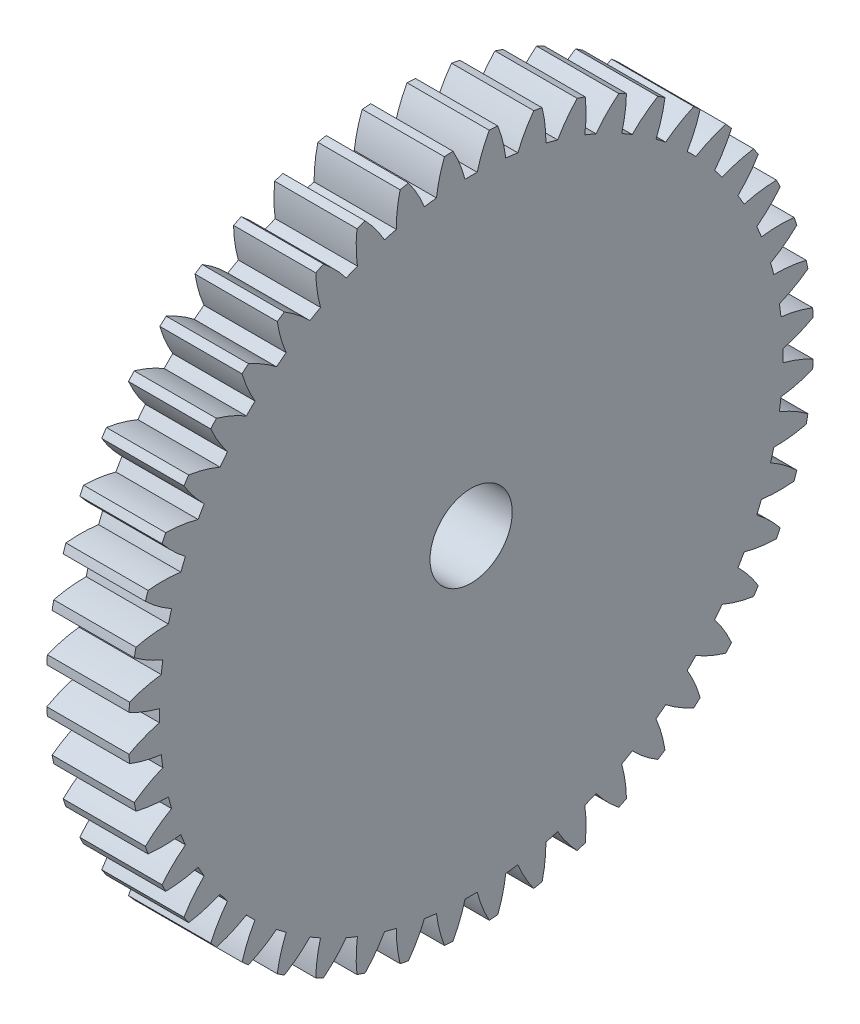
SolidWorks part; units mm, degrees
ref_plane "Plane1" through (0, 0, 0) normal (0, 0, 1) x (1, 0, 0)
ref_plane "Plane2" through (0, 0, 0) normal (0, 1, 0) x (1, 0, 0)
ref_plane "Plane3" through (0, 0, 0) normal (1, 0, 0) x (0, 0, -1)
other "Configuration Table"
sketch "HoldingSke" plane through (0, 0, 0) normal (0, 1, 0) x (1, 0, 0)
  line L0 (0, 0) -> (407.902, -453.0211)
  line L1 (-15, 0) -> (100, 0) construction
  line L2 (0, 0) -> (-2.1039, 2.3779)
  line L3 (0, 0) -> (-11.863, 4.5341)
  line L4 (0, 0) -> (5.7786, 6.4178)
  line L5 (0, 0) -> (-47.5972, -17.7524)
  line L6 (0, 0) -> (-10.5278, -7.1032)
  line L7 (-2.1039, 2.3779) -> (8.8308, 51.9871)
  line L8 (-76.2, 54.61) -> (-75.184, 54.61)
  line L9 (-71.009, 38.7566) -> (-53.1078, 45.2721)
  line L10 (-76.2, 71.12) -> (104.1128, 71.12)
  line L11 (0, 0) -> (-12.7, 0)
  line L12 (-76.2, 101.6) -> (-76.1573, 101.6)
  line L13 (24.9733, 27.94) -> (52.9518, 28.4284)
  line L14 (24.9733, 27.94) -> (25.0241, 27.9398)
  line L15 (24.9733, 27.94) -> (100.4021, 29.52)
  circle A0 centre (0, 0) radius 0.3969
  circle A1 centre (0, 0) radius 24.0792
  circle A2 centre (0, 0) radius 38.1
  circle A3 centre (0, 0) radius 0.3969
  dimension "MHD" = 48.1584
  dimension "Hub_dia" = 76.2
  dimension "Bore" = 0.7937
  dimension "MBD" = 0.7937
  dimension "Num_teeth" = 48
  dimension "Pitch" = 609.6
  dimension "Overall_len" = 50.8
  dimension "Show_teeth" = 48
  dimension "Thickness" = 12.7
  dimension "OAL" = 50.8001
  dimension "T_dim" = 1.016
  dimension "Ap" = 20
  dimension "H" = 19.05
  dimension "Pitch_radius" = 180.3128
  dimension "Width" = 12.7
  dimension "Backlash" = 0.0427
  dimension "Addendum_fac" = 1
  dimension "Dedendum_fac" = 1.2
  dimension "Clearance_fac" = 0.2
  dimension "Dedendum_add" = 0.0508
sketch "BasProSke" plane through (0, 0, 0) normal (0, 1, 0) x (1, 0, 0)
  line L0 (-10, 0) -> (60, 0) construction
  line L1 (0, 0) -> (0, 26.4583)
  line L2 (0, 0) -> (6.35, 0)
  line L3 (6.35, 0) -> (6.35, 26.4583)
  line L4 (6.35, 26.4583) -> (0, 26.4583)
  dimension "Thickness" = 6.35
  dimension "Diameter" = 52.9167
revolve "Base-Revolve" add sketch "BasProSke" angle 360 about L0
sketch "TooCutSke" plane through (0, 0, 0) normal (1, 0, 0) x (0, 0, -1)
  line L1 (0, 0) -> (0, 107) construction
  line L2 (0, 0) -> (-0.9057, 25.3838) construction
  line L3 (0, 0) -> (-3.321, 50.6688) construction
  line L4 (-0.9057, 25.3838) -> (-1.6605, 25.3344) construction
  arc A0 (0.47, 24.0746) -> (-0.47, 24.0746) centre (0, 0) ccw
  arc A1 (1.4151, 26.4459) -> (-1.4151, 26.4459) centre (0, 0) ccw
  circle A2 centre (0, 0) radius 25.4 construction
  circle A3 centre (0, 0) radius 23.8682 construction
  arc A4 (-0.47, 24.0746) -> (-1.4151, 26.4459) centre (-10.3059, 21.5286) ccw
  arc A5 (1.4151, 26.4459) -> (0.47, 24.0746) centre (10.3059, 21.5286) ccw
  dimension "Root_dia" = 48.1584
  dimension "Overcut_dia" = 52.9675
  dimension "Pitch_dia" = 50.8
  dimension "Base_dia" = 47.7364
  dimension "Flank_rad" = 10.16
  dimension "Half_ang" = 3.75
  dimension "Half_CT" = 0.7564
extrude "ToothCut" cut sketch "TooCutSke" along normal through all
fillet "Breaks" [suppressed] radius 0.0212
fillet "RootFillets" [suppressed] radius 0.2625
pattern_circular "TeethCuts" count 48 every 7.5 about axis through (-10, 0, 0) along (1, 0, 0) of "ToothCut", "RootFillets", "Breaks"
sketch "HubNeaOneSke" plane through (0, 0, 0) normal (-1, 0, 0) x (0, 0, 1)
  circle A0 centre (0, 0) radius 24.0792
  dimension "Diameter" = 48.1584
extrude "HubNearOne" [suppressed] add sketch "HubNeaOneSke" along normal blind 44.4501
sketch "HubNeaBotSke" plane through (0, 0, 0) normal (-1, 0, 0) x (0, 0, 1)
  circle A0 centre (0, 0) radius 24.0792
  dimension "Diameter" = 48.1584
extrude "HubNearBoth" [suppressed] add sketch "HubNeaBotSke" along normal blind 22.225
ref_plane "FarPln" through (6.35, 0, 0) normal (1, 0, 0) x (0, 0, -1)
sketch "HubFarSke" plane through (6.35, 0, 0) normal (1, 0, 0) x (0, 0, -1)
  circle A0 centre (0, 0) radius 24.0792
  dimension "Diameter" = 48.1584
extrude "HubFar" [suppressed] add sketch "HubFarSke" along normal blind 22.225
sketch "BorSke" plane through (0, 0, 0) normal (1, 0, 0) x (0, 0, -1)
  circle A0 centre (0, 0) radius 3.175
  dimension "Diameter" = 6.35
extrude "Bore" cut sketch "BorSke" along normal mid plane 101.6001
sketch "KeySke" plane through (0, 0, 0) normal (1, 0, 0) x (0, 0, -1)
  line L0 (-0.127, 0) -> (-0.127, 0.6191)
  line L1 (-0.127, 0.6191) -> (0.127, 0.6191)
  line L2 (0.127, 0.6191) -> (0.127, 0)
  line L3 (0, 0) -> (0, 34) construction
  line L4 (-0.127, 0) -> (0.127, 0)
  dimension "Offset" = 0.6191
  dimension "Width" = 0.254
extrude "Keyway" [suppressed] cut sketch "KeySke" along normal mid plane 101.6001
pattern_circular "Keyway2" [suppressed] count 2 every 90 about axis through (-10, 0, 0) along (1, 0, 0)
equation "' \"Pitch@HoldingSke\" = 4"
equation "' \"Num_teeth@HoldingSke\" = 12"
equation "' \"Ap@HoldingSke\" =  20"
equation "' \"Ap@HoldingSke\" = 20"
equation "' \"Width@HoldingSke\" = 0.5"
equation "' \"Hub_dia@HoldingSke\"= 1"
equation "' \"Hub_dia@HoldingSke\" = 1"
equation "' \"Overall_len@HoldingSke\" = 1.0"
equation "' \"Bore@HoldingSke\" = 0.75"
equation "' \"T_dim@HoldingSke\" = 0.85"
equation "' \"Width@KeySke\" = 0.25"
equation "' \"Show_teeth@HoldingSke\" = 13"
equation "' \"Backlash@HoldingSke\" = 0.009"
equation "' \"Addendum_fac@HoldingSke\" = 1.0"
equation "' \"Dedendum_fac@HoldingSke\" = 1.25"
equation "' \"Dedendum_add@HoldingSke\" = 0.00005"
equation "' \"Clearance_fac@HoldingSke\" = 0.25"
equation "' \"Pitch@HoldingSke\" = 0.5"
equation "' \"Num_teeth@HoldingSke\" = 23"
equation "' \"Show_teeth@HoldingSke\" = 23"
equation "' \"Backlash@HoldingSke\" = 0.0375"
equation "\"Overcut_dia@TooCutSke\" = (\"Num_teeth@HoldingSke\" + 2 * \"Addendum_fac@HoldingSke\") / \"Pitch@HoldingSke\" + 0.002"
equation "\"Pitch_dia@TooCutSke\" = \"Num_teeth@HoldingSke\" / \"Pitch@HoldingSke\""
equation "\"Base_dia@TooCutSke\" = \"Num_teeth@HoldingSke\" / \"Pitch@HoldingSke\" * cos((\"Ap@HoldingSke\"  * 3.14159265 / 180))"
equation "\"Root_dia@TooCutSke\" = (\"Num_teeth@HoldingSke\" + 2) / \"Pitch@HoldingSke\" - 2 * (\"Addendum_fac@HoldingSke\" + \"Dedendum_fac@HoldingSke\") / \"Pitch@HoldingSke\" - \"Dedendum_add@HoldingSke\" * 2"
equation "\"Half_ang@TooCutSke\" = 180 / \"Num_teeth@HoldingSke\""
equation "\"Half_CT@TooCutSke\" = \"Num_teeth@HoldingSke\" / \"Pitch@HoldingSke\" * sin((3.14159265 / 2 / \"Num_teeth@HoldingSke\")) / 2 - 7 * \"Backlash@HoldingSke\" / 4"
equation "\"Flank_rad@TooCutSke\" = \"Num_teeth@HoldingSke\" / \"Pitch@HoldingSke\" / 5"
equation "\"Radius@RootFillets\" = \"Clearance_fac@HoldingSke\" / \"Pitch@HoldingSke\" + \"Dedendum_add@HoldingSke\""
equation "\"Break_rad@Breaks\" = 0.02 / \"Pitch@HoldingSke\""
equation "\"Thickness@HoldingSke\" = \"Width@HoldingSke\""
equation "\"OAL@HoldingSke\" = \"Thickness@HoldingSke\""
equation "\"MHD@HoldingSke\" = (\"Num_teeth@HoldingSke\" + 2) / \"Pitch@HoldingSke\" - 2 * (\"Addendum_fac@HoldingSke\" + \"Dedendum_fac@HoldingSke\")  / \"Pitch@HoldingSke\" - \"Dedendum_add@HoldingSke\" * 2"
equation "\"MBD@HoldingSke\" = (\"Num_teeth@HoldingSke\" + 2) / \"Pitch@HoldingSke\" - 2 * (\"Addendum_fac@HoldingSke\" + \"Dedendum_fac@HoldingSke\")  / \"Pitch@HoldingSke\" - \"Dedendum_add@HoldingSke\" * 2 - 0.002"
equation "\"MHD@HoldingSke\" = ((sgn( \"MHD@HoldingSke\" - \"Hub_dia@HoldingSke\" )-1)*( \"MHD@HoldingSke\" - \"Hub_dia@HoldingSke\" ))/-2+ \"Hub_dia@HoldingSke\""
equation "\"MBD@HoldingSke\" = ((sgn( \"MBD@HoldingSke\" - \"Bore@HoldingSke\" )-1)*( \"MBD@HoldingSke\" - \"Bore@HoldingSke\" ))/-2+ \"Bore@HoldingSke\""
equation "\"OAL@HoldingSke\" = ((sgn( \"OAL@HoldingSke\" - \"Overall_len@HoldingSke\" )+1)*( \"OAL@HoldingSke\" - \"Overall_len@HoldingSke\" ))/2 + \"Overall_len@HoldingSke\" + 0.000002"
equation "\"Num_teeth@TeethCuts\" = int( \"Show_teeth@HoldingSke\" ) + 1"
equation "\"Num_teeth@TeethCuts\" = ((sgn( \"Num_teeth@TeethCuts\" - \"Num_teeth@HoldingSke\" )-1)*( \"Num_teeth@TeethCuts\" - \"Num_teeth@HoldingSke\" ))/-2+ \"Num_teeth@HoldingSke\""
equation "\"Num_teeth@TeethCuts\" = ((sgn( \"Num_teeth@TeethCuts\" - 2.0)+1)*( \"Num_teeth@TeethCuts\" - 2.0))/2 +2.0"
equation "\"Angle@TeethCuts\" = 360.0 / \"Num_teeth@HoldingSke\""
equation "\"Diameter@BasProSke\" = (\"Num_teeth@HoldingSke\" + 2 * \"Addendum_fac@HoldingSke\") / \"Pitch@HoldingSke\""
equation "' \"Fillet_rad@BasProSke\" =  \"Thickness@HoldingSke\" * 0.05"
equation "' \"Fillet_rad@BasProSke\" = \"Thickness@HoldingSke\" * 0.05"
equation "\"MHD@HoldingSke\" = ((sgn( \"MHD@HoldingSke\" - \"Root_dia@TooCutSke\" )-1)*( \"MHD@HoldingSke\" - \"Root_dia@TooCutSke\" ))/-2+ \"Root_dia@TooCutSke\""
equation "\"Diameter@HubNeaOneSke\" = \"MHD@HoldingSke\""
equation "\"Length@HubNearOne\" = \"OAL@HoldingSke\" - \"Thickness@BasProSke\""
equation "\"Diameter@HubNeaBotSke\" = \"MHD@HoldingSke\""
equation "\"Length@HubNearBoth\" = ( \"OAL@HoldingSke\" - \"Thickness@BasProSke\" ) / 2.0"
equation "\"Thickness@FarPln\" = \"Thickness@BasProSke\""
equation "\"Diameter@HubFarSke\" = \"MHD@HoldingSke\""
equation "\"Length@HubFar\" = ( \"OAL@HoldingSke\" - \"Thickness@BasProSke\" ) / 2.0"
equation "\"D1@Bore\" = \"OAL@HoldingSke\" * 2.0"
equation "\"D1@Keyway\" = \"OAL@HoldingSke\" * 2.0"
equation "\"Offset@KeySke\" = \"T_dim@HoldingSke\" - \"MBD@HoldingSke\" / 2.0"
